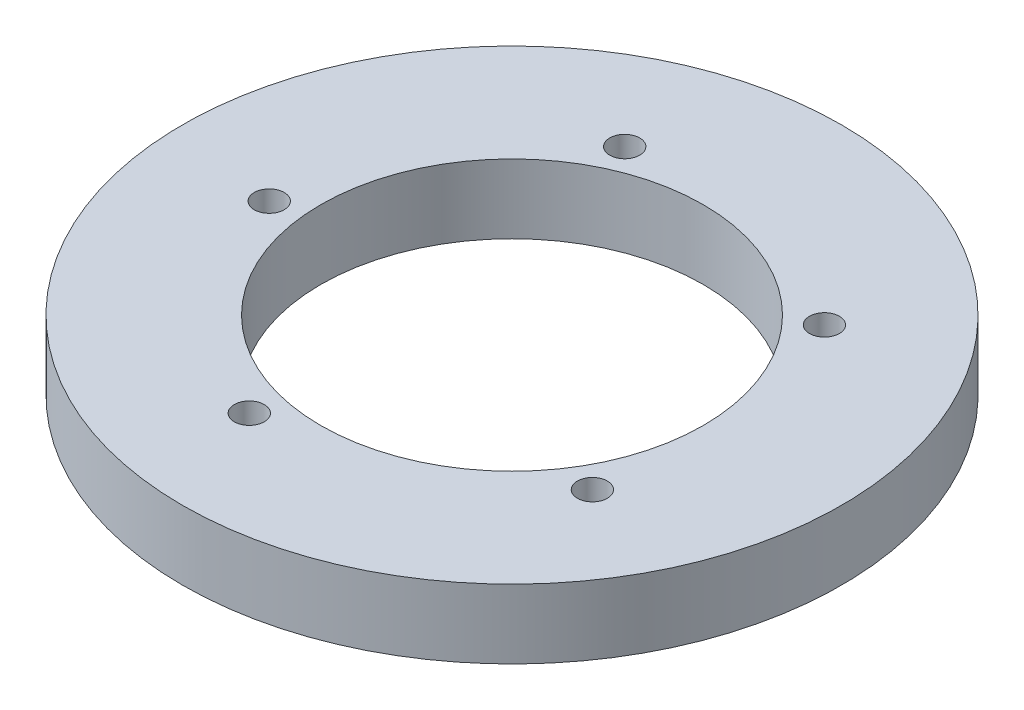
SolidWorks part; units mm, degrees
material "ABS PC"
ref_plane "Front Plane" through (0, 0, 0) normal (0, 0, 1) x (1, 0, 0)
ref_plane "Top Plane" through (0, 0, 0) normal (0, 1, 0) x (1, 0, 0)
ref_plane "Right Plane" through (0, 0, 0) normal (1, 0, 0) x (0, 0, -1)
sketch "Sketch1" plane through (0, 0, 0) normal (0, 1, 0) x (1, 0, 0)
  circle A0 centre (-1.3362, 19.9052) radius 41.5
  circle A1 centre (-1.3362, 19.9052) radius 71.5
  circle A2 centre (40.1859, -4.1762) radius 3.25
  circle A3 centre (34.3976, 51.9535) radius 3.25
  circle A4 centre (-20.7736, 63.7936) radius 3.25
  circle A5 centre (-49.083, 14.9815) radius 3.25
  circle A6 centre (-11.408, -27.0262) radius 3.25
  circle A7 centre (-1.3362, 19.9052) radius 41.5 construction
  point P21 (0, 0)
  point P22 (-41.0674, 46.4623)
  point P23 (0, 0)
  point P24 (8.9017, 66.1102)
  point P26 (-41.0674, 46.4623)
  point P28 (0, 0)
  point P29 (45.9217, 26.5762)
  point P31 (0, 0)
  point P32 (19.2229, -22.5397)
  point P34 (0, 0)
  point P35 (-34.7622, -12.5036)
  point P37 (0, 0)
  dimension "D1" = 6.5
  dimension "D2" = 30
extrude "Boss-Extrude1" add sketch "Sketch1" along normal blind 15
